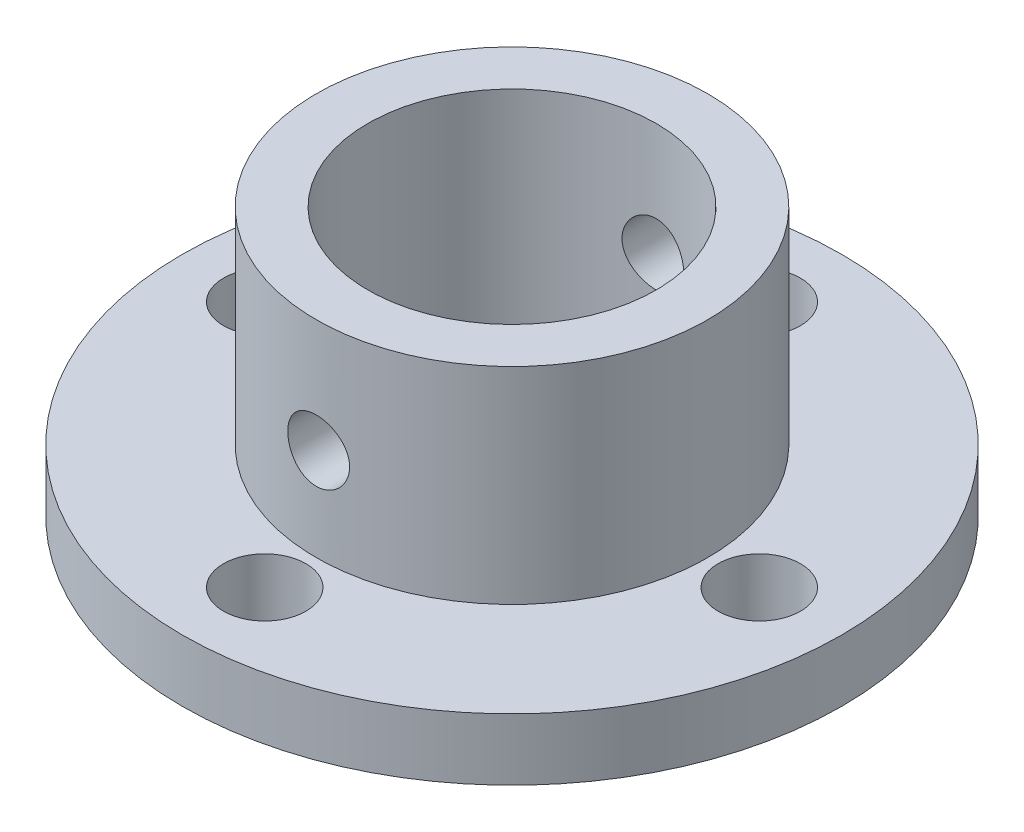
SolidWorks part; units mm, degrees
ref_plane "Front Plane" through (0, 0, 0) normal (0, 0, 1) x (1, 0, 0)
ref_plane "Top Plane" through (0, 0, 0) normal (0, 1, 0) x (1, 0, 0)
ref_plane "Right Plane" through (0, 0, 0) normal (1, 0, 0) x (0, 0, -1)
sketch "Sketch1" plane through (0, 0, 0) normal (1, 0, 0) x (0, 0, -1)
  line L0 (0, 0) -> (0, 8479.52) construction
  line L1 (-7, 0) -> (-16, 0)
  line L2 (-16, 0) -> (-16, 3)
  line L3 (-16, 3) -> (-9.5, 3)
  line L4 (-9.5, 3) -> (-9.5, 13)
  line L5 (-9.5, 13) -> (-7, 13)
  line L6 (-7, 13) -> (-7, 0)
revolve "Revolve1" add sketch "Sketch1" angle 360 about L0
sketch "Sketch2" plane through (0, 0, 0) normal (0, 0, 1) x (1, 0, 0)
  circle A0 centre (0, 7.5) radius 1.5
  dimension "D1" = 3
extrude "Cut-Extrude1" cut sketch "Sketch2" against normal through all both and the other way through all
sketch "Sketch3" plane through (0, 3, 0) normal (0, 1, 0) x (1, 0, 0)
  circle A0 centre (0, 0) radius 12 construction
  circle A1 centre (0, -12) radius 2
extrude "Cut-Extrude2" cut sketch "Sketch3" against normal through all both and the other way through all
pattern_circular "CirPattern1" count 4 over 360 about axis through (0, 0, 0) along (0, 1, 0) of "Cut-Extrude2"
